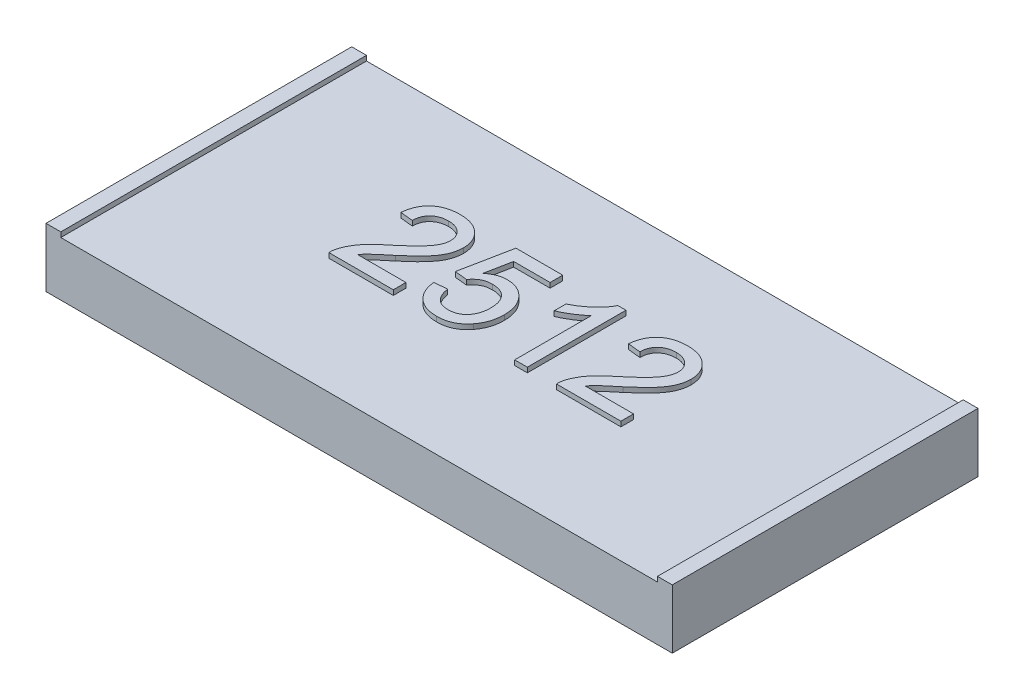
SolidWorks part; units mm, degrees
ref_plane "Спереди" through (0, 0, 0) normal (0, 0, 1) x (1, 0, 0)
ref_plane "Сверху" through (0, 0, 0) normal (0, 1, 0) x (1, 0, 0)
ref_plane "Справа" through (0, 0, 0) normal (1, 0, 0) x (0, 0, -1)
sketch "Эскиз1" plane through (0, 0, 0) normal (0, 1, 0) x (1, 0, 0)
  line L1 (-3.175, 1.55) -> (3.175, 1.55)
  line L2 (-3.175, 1.55) -> (-3.175, -1.55)
  line L3 (-3.175, -1.55) -> (3.175, -1.55)
  line L4 (3.175, 1.55) -> (3.175, -1.55)
  line L5 (-3.175, 1.55) -> (3.175, -1.55) construction
  line L6 (-3.175, -1.55) -> (3.175, 1.55) construction
  point P0 (0, 0)
  dimension "D1" = 3.1
  dimension "D2" = 6.35
extrude "Бобышка-Вытянуть1" add sketch "Эскиз1" along normal blind 0.55
sketch "Эскиз2" plane through (0, 0.55, 0) normal (0, 1, 0) x (1, 0, 0)
  line L0 (-3.175, -1.55) -> (3.175, -1.55) construction
  line L1 (-3.175, 1.55) -> (-3.025, 1.55)
  line L2 (-3.175, 1.55) -> (-3.175, -1.55)
  line L3 (-3.175, -1.55) -> (-3.025, -1.55)
  line L4 (-3.025, 1.55) -> (-3.025, -1.55)
  line L6 (3.175, 1.55) -> (3.025, 1.55)
  line L7 (3.175, 1.55) -> (3.175, -1.55)
  line L8 (3.175, -1.55) -> (3.025, -1.55)
  line L9 (3.025, 1.55) -> (3.025, -1.55)
  dimension "D1" = 0.15
  dimension "D2" = 0.15
extrude "Бобышка-Вытянуть2" add sketch "Эскиз2" along normal blind 0.05
sketch "Эскиз3" plane through (0, 0.55, 0) normal (0, 1, 0) x (1, 0, 0)
  text T0 "2512" font "Arial" height 1
extrude "Бобышка-Вытянуть3" add sketch "Эскиз3" along normal blind 0.05
